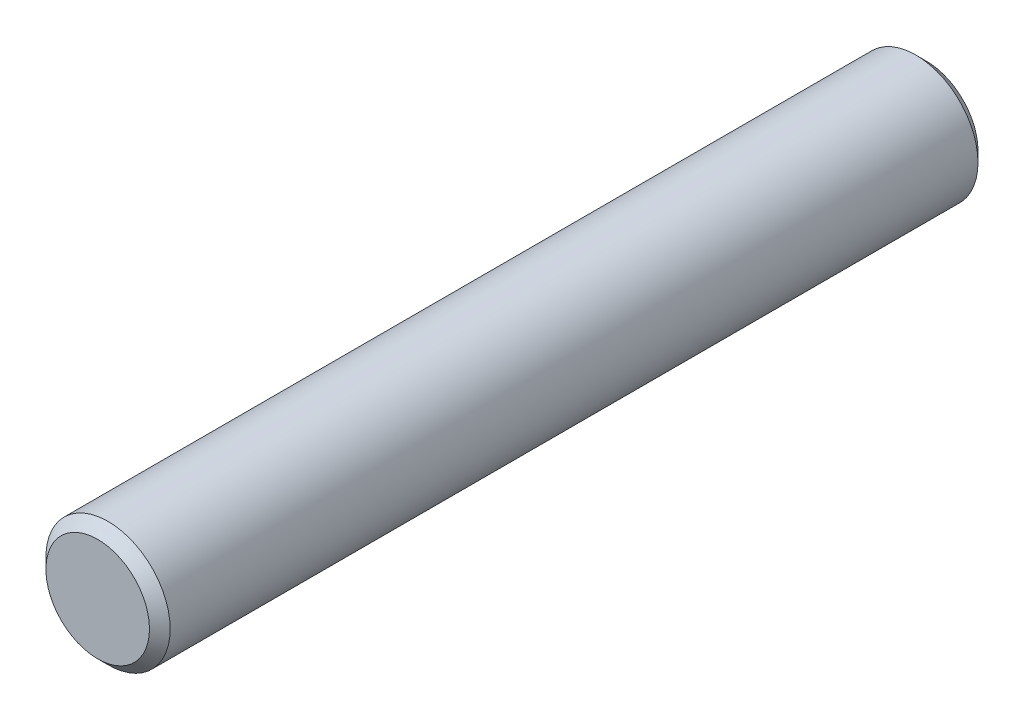
SolidWorks part; units mm, degrees
material "Plain Carbon Steel"
ref_plane "Спереди" through (0, 0, 0) normal (0, 0, 1) x (1, 0, 0)
ref_plane "Сверху" through (0, 0, 0) normal (0, 1, 0) x (1, 0, 0)
ref_plane "Справа" through (0, 0, 0) normal (1, 0, 0) x (0, 0, -1)
sketch "Sketch1" plane through (0, 0, 0) normal (0, 0, 1) x (1, 0, 0)
  circle A0 centre (0, 0) radius 3
  dimension "D1" = 6
extrude "Boss-Extrude1" add sketch "Sketch1" along normal blind 40
chamfer "Chamfer1" distance 0.5 angle 45 2 edges at (3, 0, 40) (3, 0, 0)
